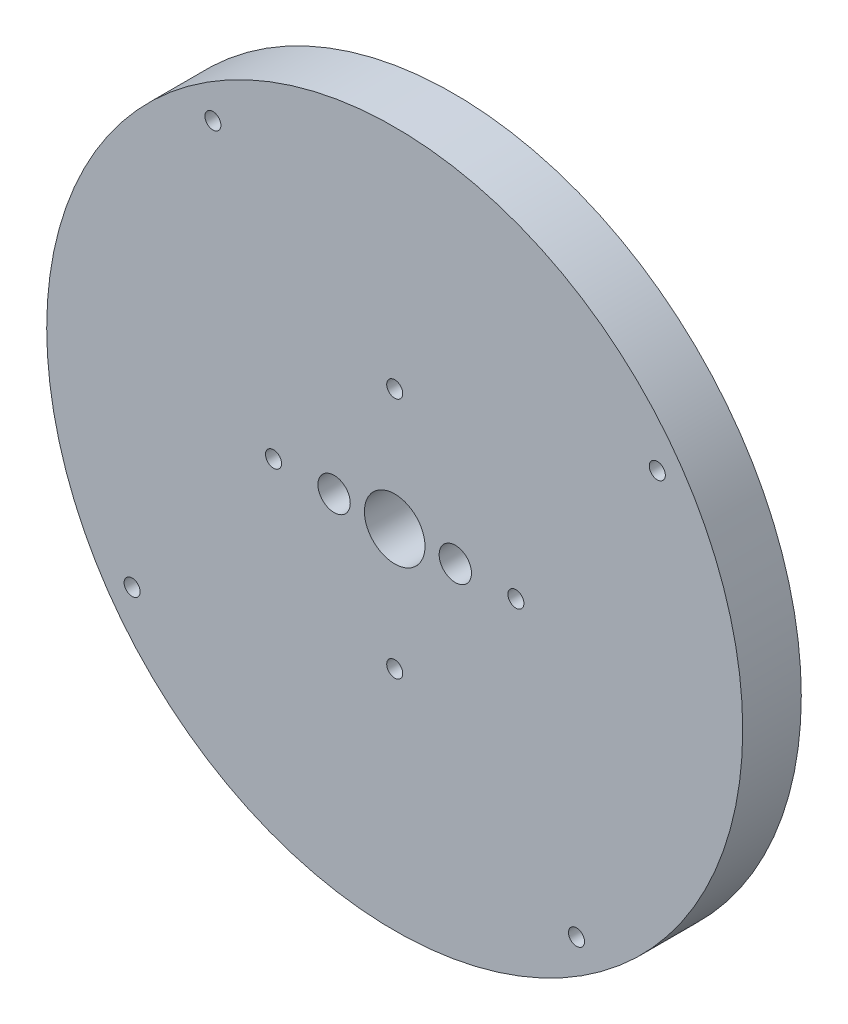
SolidWorks part; units mm, degrees
material "Balsa"
ref_plane "Front Plane" through (0, 0, 0) normal (0, 0, 1) x (1, 0, 0)
ref_plane "Top Plane" through (0, 0, 0) normal (0, 1, 0) x (1, 0, 0)
ref_plane "Right Plane" through (0, 0, 0) normal (1, 0, 0) x (0, 0, -1)
sketch "Sketch1" plane through (0, 0, 0) normal (0, 0, 1) x (1, 0, 0)
  circle A0 centre (0, 0) radius 34.4583
  circle A1 centre (0, 0) radius 3
  dimension "D1" = 68.9167
  dimension "D2" = 6
extrude "Boss-Extrude1" add sketch "Sketch1" along normal blind 5.8
sketch "Sketch2" plane through (0, 0, 5.8) normal (0, 0, 1) x (1, 0, 0)
  line L0 (0, 0) -> (0, 12) construction
  line L1 (-18, 26) -> (0, 0) construction
  line L2 (0, 0) -> (26, 18) construction
  line L3 (0, 0) -> (18, -26) construction
  circle A0 centre (0, 12) radius 0.7937
  circle A1 centre (12, 0) radius 0.7937
  circle A2 centre (0, -12) radius 0.7937
  circle A3 centre (-12, 0) radius 0.7937
  circle A4 centre (0, 0) radius 12 construction
  circle A5 centre (-18, 26) radius 0.7937
  circle A6 centre (26, 18) radius 0.7938
  circle A7 centre (18, -26) radius 0.7937
  circle A8 centre (-26, -18) radius 0.7937
  dimension "D1" = 1.5875
  dimension "D2" = 12
  dimension "D4" = 18
  dimension "D5" = 26
  dimension "D3" = 4
  dimension "D6" = 4
extrude "Cut-Extrude1" cut sketch "Sketch2" against normal through all
hole_wizard "M3 Clearance Hole1" positions "Sketch4" profile "Sketch3" hole size "M3" standard "Ansi Metric"
sketch "Sketch4" plane through (0, 0, 5.8) normal (0, 0, 1) x (1, 0, 0)
  line L0 (0, 0) -> (-6, 0) construction
  line L2 (0, 0) -> (0, 7.4447) construction
  point P18 (-6, 0)
  point P22 (6, 0)
  dimension "D1" = 6
sketch "Sketch3" plane through (-6, 0, 5.8) normal (1, 0, 0) x (0, -1, 0)
  line L0 (0, 0) -> (0, 13.6614)
  line L1 (0, 13.6614) -> (1.6, 12.7)
  line L2 (1.6, 12.7) -> (1.6, 0)
  line L5 (1.6, 0) -> (0, 0)
  line L10 (0, 13.6614) -> (-1.6, 12.7) construction
  line L11 (0, -6.35) -> (0, 107.95) construction
  dimension "Hole Dia." = 3.2
  dimension "Hole Depth" = 12.7
  dimension "Drill Angle" = 118
